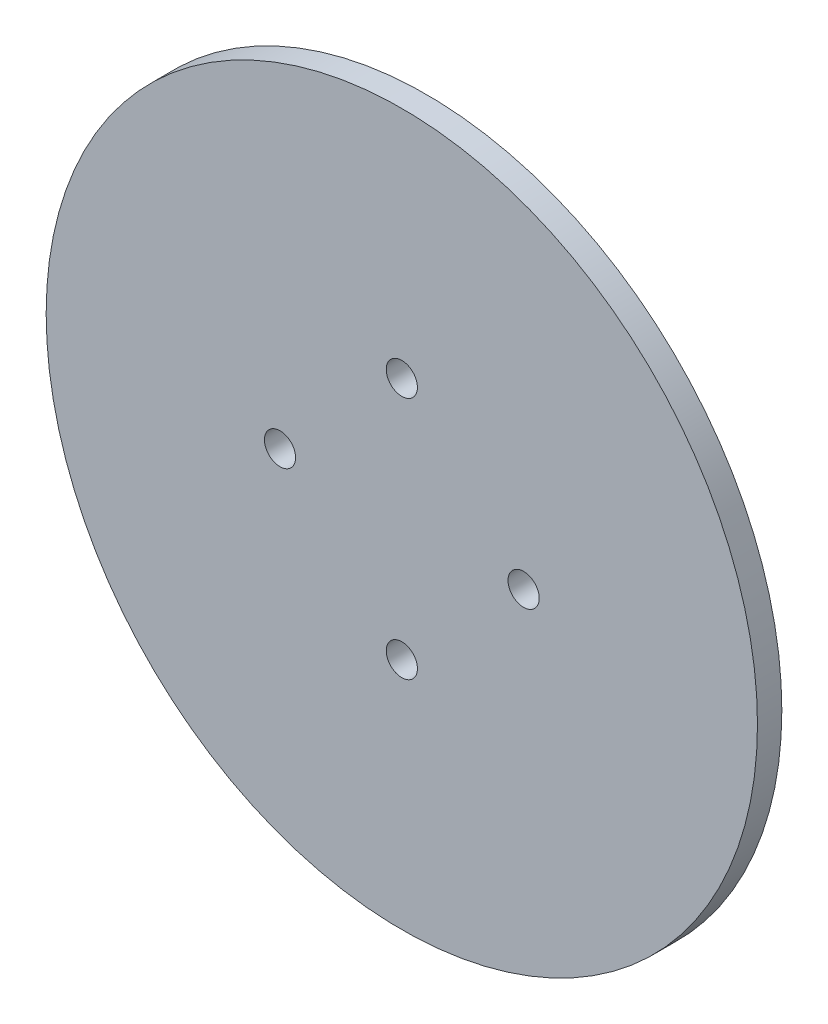
SolidWorks part; units mm, degrees
material "ABS"
ref_plane "Płaszczyzna przednia" through (0, 0, 0) normal (0, 0, 1) x (1, 0, 0)
ref_plane "Płaszczyzna górna" through (0, 0, 0) normal (0, 1, 0) x (1, 0, 0)
ref_plane "Płaszczyzna prawa" through (0, 0, 0) normal (1, 0, 0) x (0, 0, -1)
sketch "Szkic1" plane through (0, 0, 0) normal (0, 0, 1) x (1, 0, 0)
  line L0 (0, 0) -> (51.1373, 70.3845) construction
  line L1 (0, 0) -> (0, 87) construction
  line L2 (-1.4751, 37) -> (1.4751, 37)
  line L3 (-2.3701, 67) -> (2.3701, 67)
  line L4 (-6.4502, 41.5025) -> (-8.3403, 60.403)
  line L5 (6.4502, 41.5025) -> (8.3403, 60.403)
  line L6 (29.6563, 29.9183) -> (42.2948, 44.0981)
  line L7 (37.5075, 55.7306) -> (41.3424, 52.9445)
  line L8 (19.2195, 37.501) -> (28.7999, 53.9028)
  line L9 (20.5981, 30.9341) -> (22.9848, 29.2)
  line L10 (41.6213, 6.9063) -> (60.1808, 10.9493)
  line L11 (63.1452, 23.1741) -> (64.61, 18.6659)
  line L12 (37.6348, 19.1754) -> (55.0262, 26.8135)
  line L13 (34.8901, 13.0524) -> (35.8017, 10.2466)
  line L14 (37.7751, -18.7437) -> (55.1665, -26.3818)
  line L15 (64.7503, -18.2342) -> (63.2855, -22.7424)
  line L16 (41.7616, -6.4746) -> (60.321, -10.5176)
  line L17 (35.942, -9.8149) -> (35.0304, -12.6206)
  line L18 (19.5868, -37.2342) -> (29.1671, -53.6359)
  line L19 (41.7096, -52.6776) -> (37.8748, -55.4638)
  line L20 (30.0235, -29.6514) -> (42.662, -43.8313)
  line L21 (23.352, -28.9332) -> (20.9653, -30.6672)
  line L22 (-5.9963, -41.5025) -> (-7.8864, -60.403)
  line L23 (2.824, -67) -> (-1.9161, -67)
  line L24 (6.9042, -41.5025) -> (8.7942, -60.403)
  line L25 (1.929, -37) -> (-1.0211, -37)
  line L26 (-29.2023, -29.9183) -> (-41.8408, -44.0981)
  line L27 (-37.0536, -55.7306) -> (-40.8884, -52.9445)
  line L28 (-18.7656, -37.501) -> (-28.3459, -53.9028)
  line L29 (-20.1441, -30.9341) -> (-22.5308, -29.2)
  line L30 (-41.1673, -6.9063) -> (-59.7268, -10.9493)
  line L31 (-62.6913, -23.1741) -> (-64.1561, -18.6659)
  line L32 (-37.1809, -19.1754) -> (-54.5722, -26.8135)
  line L33 (-34.4362, -13.0524) -> (-35.3478, -10.2466)
  line L34 (-37.3211, 18.7437) -> (-54.7125, 26.3818)
  line L35 (-64.2963, 18.2342) -> (-62.8316, 22.7424)
  line L36 (-41.3076, 6.4746) -> (-59.8671, 10.5176)
  line L37 (-35.4881, 9.8149) -> (-34.5764, 12.6206)
  line L38 (-19.1328, 37.2342) -> (-28.7132, 53.6359)
  line L39 (-41.2557, 52.6776) -> (-37.4208, 55.4638)
  line L40 (-29.5696, 29.6514) -> (-42.2081, 43.8313)
  line L41 (-22.8981, 28.9332) -> (-20.5114, 30.6672)
  circle A0 centre (0, 0) radius 79 construction
  circle A2 centre (0, 0) radius 25 construction
  circle A3 centre (0, 0) radius 3.3
  circle A4 centre (0, 25) radius 3.2
  circle A5 centre (0, 79) radius 1.9
  circle A6 centre (25, 0) radius 3.2
  circle A7 centre (0, -25) radius 3.2
  circle A8 centre (-25, 0) radius 3.2
  circle A9 centre (75.1335, 24.4123) radius 1.9
  circle A10 centre (46.435, -63.9123) radius 1.9
  circle A11 centre (-46.435, -63.9123) radius 1.9
  circle A12 centre (-75.1335, 24.4123) radius 1.9
  circle A13 centre (0, 0) radius 87 construction
  arc A14 (8.3403, 60.403) -> (2.3701, 67) centre (2.3701, 61) ccw
  arc A15 (-2.3701, 67) -> (-8.3403, 60.403) centre (-2.3701, 61) ccw
  arc A16 (6.4502, 41.5025) -> (1.4751, 37) centre (1.4751, 42) cw
  arc A17 (-6.4502, 41.5025) -> (-1.4751, 37) centre (-1.4751, 42) ccw
  arc A18 (29.6563, 29.9183) -> (22.9848, 29.2) centre (25.9237, 33.2451) cw
  arc A19 (42.2948, 44.0981) -> (41.3424, 52.9445) centre (37.8157, 48.0904) ccw
  arc A20 (37.5075, 55.7306) -> (28.7999, 53.9028) centre (33.9808, 50.8765) ccw
  arc A21 (19.2195, 37.501) -> (20.5981, 30.9341) centre (23.537, 34.9791) ccw
  arc A22 (41.6213, 6.9063) -> (35.8017, 10.2466) centre (40.557, 11.7917) cw
  arc A23 (60.1808, 10.9493) -> (64.61, 18.6659) centre (58.9037, 16.8118) ccw
  arc A24 (63.1452, 23.1741) -> (55.0262, 26.8135) centre (57.4389, 21.32) ccw
  arc A25 (37.6348, 19.1754) -> (34.8901, 13.0524) centre (39.6454, 14.5974) ccw
  arc A26 (37.7751, -18.7437) -> (35.0304, -12.6206) centre (39.7857, -14.1657) cw
  arc A27 (55.1665, -26.3818) -> (63.2855, -22.7424) centre (57.5792, -20.8882) ccw
  arc A28 (64.7503, -18.2342) -> (60.321, -10.5176) centre (59.044, -16.3801) ccw
  arc A29 (41.7616, -6.4746) -> (35.942, -9.8149) centre (40.6973, -11.36) ccw
  arc A30 (19.5868, -37.2342) -> (20.9653, -30.6672) centre (23.9042, -34.7123) cw
  arc A31 (29.1671, -53.6359) -> (37.8748, -55.4638) centre (34.3481, -50.6097) ccw
  arc A32 (41.7096, -52.6776) -> (42.662, -43.8313) centre (38.1829, -47.8235) ccw
  arc A33 (30.0235, -29.6514) -> (23.352, -28.9332) centre (26.2909, -32.9783) ccw
  arc A34 (-5.9963, -41.5025) -> (-1.0211, -37) centre (-1.0211, -42) cw
  arc A35 (-7.8864, -60.403) -> (-1.9161, -67) centre (-1.9161, -61) ccw
  arc A36 (2.824, -67) -> (8.7942, -60.403) centre (2.824, -61) ccw
  arc A37 (6.9042, -41.5025) -> (1.929, -37) centre (1.929, -42) ccw
  arc A38 (-29.2023, -29.9183) -> (-22.5308, -29.2) centre (-25.4697, -33.2451) cw
  arc A39 (-41.8408, -44.0981) -> (-40.8884, -52.9445) centre (-37.3617, -48.0904) ccw
  arc A40 (-37.0536, -55.7306) -> (-28.3459, -53.9028) centre (-33.5269, -50.8765) ccw
  arc A41 (-18.7656, -37.501) -> (-20.1441, -30.9341) centre (-23.083, -34.9791) ccw
  arc A42 (-41.1673, -6.9063) -> (-35.3478, -10.2466) centre (-40.1031, -11.7917) cw
  arc A43 (-59.7268, -10.9493) -> (-64.1561, -18.6659) centre (-58.4497, -16.8118) ccw
  arc A44 (-62.6913, -23.1741) -> (-54.5722, -26.8135) centre (-56.9849, -21.32) ccw
  arc A45 (-37.1809, -19.1754) -> (-34.4362, -13.0524) centre (-39.1914, -14.5974) ccw
  arc A46 (-37.3211, 18.7437) -> (-34.5764, 12.6206) centre (-39.3317, 14.1657) cw
  arc A47 (-54.7125, 26.3818) -> (-62.8316, 22.7424) centre (-57.1252, 20.8882) ccw
  arc A48 (-64.2963, 18.2342) -> (-59.8671, 10.5176) centre (-58.59, 16.3801) ccw
  arc A49 (-41.3076, 6.4746) -> (-35.4881, 9.8149) centre (-40.2434, 11.36) ccw
  arc A50 (-19.1328, 37.2342) -> (-20.5114, 30.6672) centre (-23.4503, 34.7123) cw
  arc A51 (-28.7132, 53.6359) -> (-37.4208, 55.4638) centre (-33.8941, 50.6097) ccw
  arc A52 (-41.2557, 52.6776) -> (-42.2081, 43.8313) centre (-37.729, 47.8235) ccw
  arc A53 (-29.5696, 29.6514) -> (-22.8981, 28.9332) centre (-25.837, 32.9783) ccw
  circle A54 centre (0, 0) radius 73
  spline S0 degree 3 poles (0, 87) (18.2248, 86.9986) (32.2889, 73.5369) (46.435, 63.9123) knots 0 0 0 0 1 1 1 1
  spline S1 degree 3 poles (82.7419, 26.8845) (77.1088, 44.2169) (59.9599, 53.4327) (46.435, 63.9123) knots 0 0 0 0 1 1 1 1
  spline S2 degree 3 poles (82.7419, 26.8845) (88.3724, 9.5512) (79.9156, -7.9844) (75.1335, -24.4123) knots 0 0 0 0 1 1 1 1
  spline S3 degree 3 poles (51.1373, -70.3845) (65.8807, -59.6711) (69.3462, -40.5137) (75.1335, -24.4123) knots 0 0 0 0 1 1 1 1
  spline S4 degree 3 poles (51.1373, -70.3845) (36.3923, -81.0957) (17.1016, -78.4715) (0, -79) knots 0 0 0 0 1 1 1 1
  spline S5 degree 3 poles (-51.1373, -70.3845) (-36.3923, -81.0957) (-17.1016, -78.4715) (0, -79) knots 0 0 0 0 1 1 1 1
  spline S6 degree 3 poles (-51.1373, -70.3845) (-65.8807, -59.6711) (-69.3462, -40.5137) (-75.1335, -24.4123) knots 0 0 0 0 1 1 1 1
  spline S7 degree 3 poles (-82.7419, 26.8845) (-88.3724, 9.5512) (-79.9156, -7.9844) (-75.1335, -24.4123) knots 0 0 0 0 1 1 1 1
  spline S8 degree 3 poles (-82.7419, 26.8845) (-77.1088, 44.2169) (-59.9599, 53.4327) (-46.435, 63.9123) knots 0 0 0 0 1 1 1 1
  spline S9 degree 3 poles (0, 87) (-18.2248, 86.9986) (-32.2889, 73.5369) (-46.435, 63.9123) knots 0 0 0 0 1 1 1 1
  point P18 (0, 0)
  point P27 (0, 0)
  point P43 (0, 37)
  point P64 (0, 0)
  point P65 (0, 67)
  point P67 (9, 67)
  point P70 (-9, 67)
  point P73 (6, 37)
  point P76 (-6, 37)
  point P188 (0.227, 0)
  dimension "D1" = 158
  dimension "D2" = 6.6
  dimension "D3" = 50
  dimension "D4" = 3.8
  dimension "D5" = 6.4
  dimension "D8" = 174
  dimension "D13" = 37
  dimension "D14" = 6
  dimension "D15" = 5
  dimension "D17" = 146
  dimension "D9" = 36
  dimension "D10" = 12
  dimension "D11" = 18
  dimension "D12" = 30
  dimension "D6" = 4
  dimension "D7" = 5
  dimension "D16" = 10
extrude "Dodanie-wyciągnięcie1" add sketch "Szkic1" along normal blind 5 contours S0 S9 S8 S7 S6 S5 S4 S3 S2 S1 A3 A4 A5 A6 A7 A8 A9 A10 A11 A12 A17 L4 A15 L3 A14 L5 A16 L2 A21 L8 A20 L7 A19 L6 A18 L9 A25 L12 | L36 A49 L37 A46 L34 A47 L35 A48 | L40 A53 L41 A50 L38 A51 L39 A52 | L4 A17 L2 A16 L5 A14 L3 A15 | L8 A21 L9 A18 L6 A19 L7 A20 | L12 A25 L13 A22 L10 A23 L11 A24 | L16 A29 L17 A26 L14 A27 L15 A28 | L20 A33 L21 A30 L18 A31 L19 A32 | L24 A37 L25 A34 L22 A35 L23 A36 | L32 A45 L33 A42 L30 A43 L31 A44 | A3 | L28 A41 L29 A38 L26 A39 L27 A40
sketch "Szkic3" plane through (0, 0, 0) normal (0, 0, -1) x (-1, 0, 0)
  circle A0 centre (0, 0) radius 75
  circle A1 centre (0, 0) radius 73
  dimension "D1" = 150
  dimension "D2" = 146
extrude "Wytnij-wyciągnięcie2" [suppressed] cut sketch "Szkic3" against normal blind 2
sketch "Szkic2" plane through (0, 0, 5) normal (0, 0, 1) x (1, 0, 0)
  circle A0 centre (0, 0) radius 75
  circle A1 centre (0, 25) radius 6 construction
  circle A2 centre (25, 0) radius 6 construction
  circle A3 centre (0, -25) radius 6 construction
  circle A4 centre (-25, 0) radius 6 construction
  circle A5 centre (0, 0) radius 32.5 construction
  point P14 (0, 0)
  point P32 (0, 0)
  dimension "D1" = 150
  dimension "D2" = 12
  dimension "D3" = 4
  dimension "D4" = 65
extrude "Wytnij-wyciągnięcie1" [suppressed] cut sketch "Szkic2" against normal blind 5.5
sketch "Szkic4" [suppressed] plane through (0, 0, 0) normal (0, 0, -1) x (-1, 0, 0)
  circle A0 centre (0, 0) radius 75 construction
  circle A1 centre (0, 0) radius 75
  circle A3 centre (0, 0) radius 73
  circle A4 centre (0, 0) radius 73
  dimension "D1" = 0
extrude "Dodanie-wyciągnięcie2" [suppressed] add sketch "Szkic4" along normal blind 4
